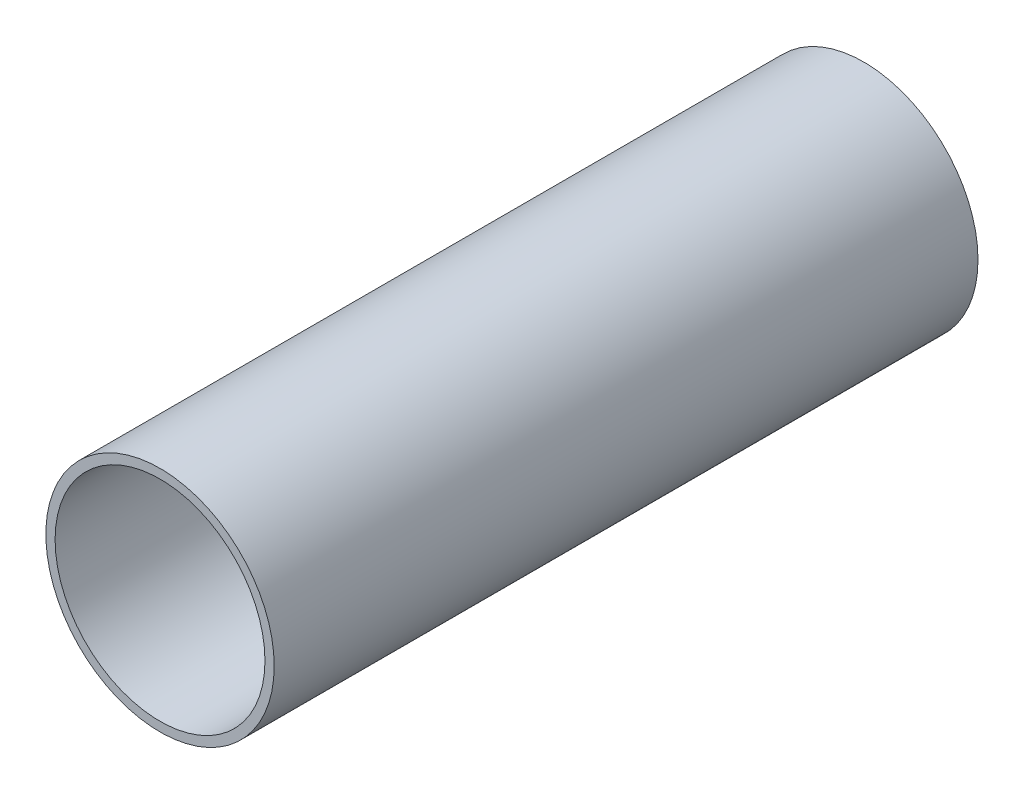
SolidWorks part; units mm, degrees
ref_plane "Front Plane" through (0, 0, 0) normal (0, 0, 1) x (1, 0, 0)
ref_plane "Top Plane" through (0, 0, 0) normal (0, 1, 0) x (1, 0, 0)
ref_plane "Right Plane" through (0, 0, 0) normal (1, 0, 0) x (0, 0, -1)
sketch "Sketch1" plane through (0, 0, 0) normal (0, 0, 1) x (1, 0, 0)
  circle A0 centre (0, 0) radius 17.272 construction
  circle A1 centre (0, 0) radius 15.875 construction
  point P4 (15.875, 0)
  point P5 (17.272, 0)
  dimension "OD" = 34.544
  dimension "ID" = 31.75
  dimension "Wall Thickness" = 1.397
sketch "Sketch2" plane through (0, 0, 0) normal (1, 0, 0) x (0, 0, -1)
  line L0 (-53.23, 0) -> (53.23, 0) construction
  line L1 (-53.23, -17.272) -> (-53.23, 17.272) construction
  line L2 (-53.23, 17.272) -> (53.23, 17.272) construction
  line L3 (53.23, -17.272) -> (53.23, 17.272) construction
  line L5 (-53.23, -17.272) -> (53.23, -17.272) construction
  point P0 (-18.686, 0)
  point P3 (0, 0)
  point P7 (0, 17.272)
  point P8 (18.686, 0)
  point P11 (-53.23, 0)
  point P13 (53.23, 0)
  dimension "Length" = 106.46
  dimension "D1" = 34.544
  dimension "D2" = 34.544
sketch "Sketch3" plane through (0, 0, 0) normal (0, 0, 1) x (1, 0, 0)
  circle A0 centre (0, 0) radius 15.875 construction
  circle A1 centre (0, 0) radius 17.272 construction
  circle A2 centre (0, 0) radius 15.875
  circle A3 centre (0, 0) radius 17.272
extrude "Boss-Extrude1" add sketch "Sketch3" along normal up to vertex (53.23 mm away) and the other way up to vertex (53.23 mm away) up to point (0, 0, 53.23) other way up to point (0, 0, -53.23)
equation "\"D1@Sketch2\"=\"OD@Sketch1\""
equation "\"D2@Sketch2\"=\"D1@Sketch2\""
